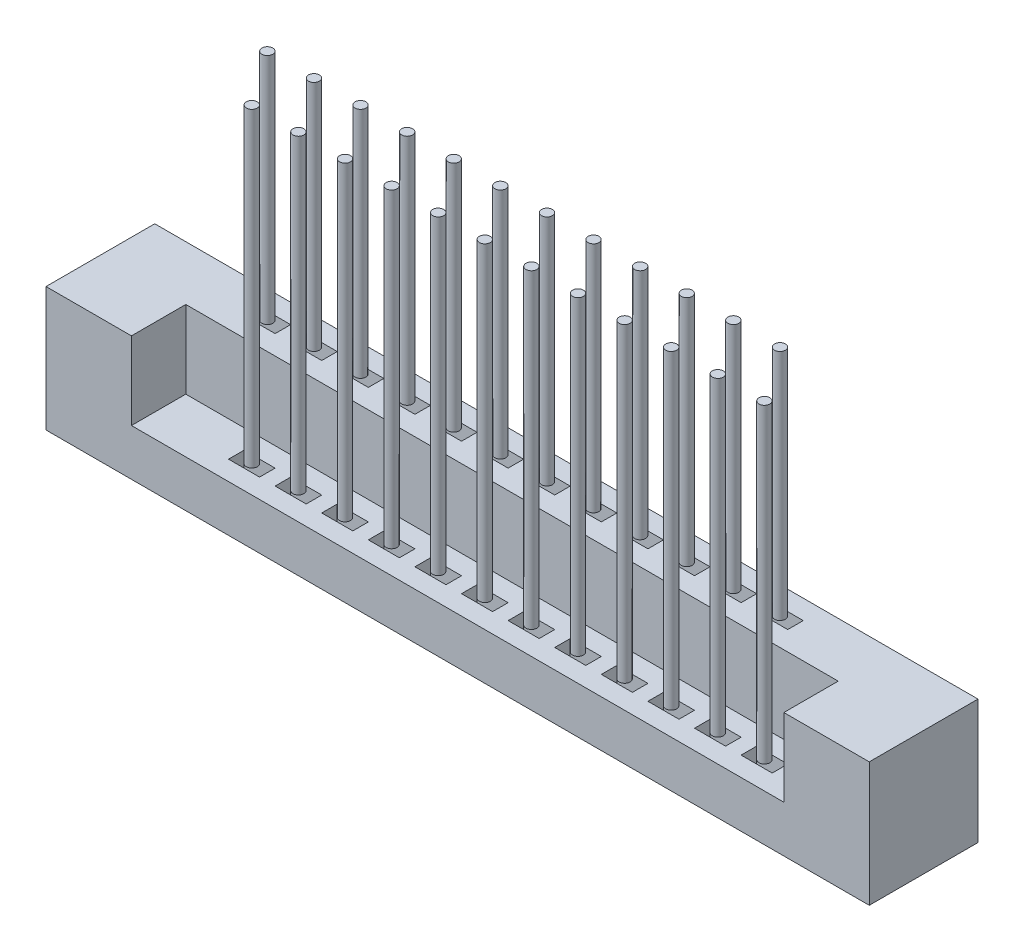
SolidWorks part; units mm, degrees
ref_plane "Front Plane" through (0, 0, 0) normal (0, 0, 1) x (1, 0, 0)
ref_plane "Top Plane" through (0, 0, 0) normal (0, 1, 0) x (1, 0, 0)
ref_plane "Right Plane" through (0, 0, 0) normal (1, 0, 0) x (0, 0, -1)
sketch "Sketch1" plane through (0, 0, 0) normal (0, 1, 0) x (1, 0, 0)
  line L1 (0, 0) -> (53, 0)
  line L2 (0, 0) -> (0, 7)
  line L3 (0, 7) -> (53, 7)
  line L4 (53, 0) -> (53, 7)
  dimension "D1" = 53
  dimension "D2" = 7
extrude "Boss-Extrude2" add sketch "Sketch1" along normal blind 8
sketch "Sketch2" plane through (0, 8, 0) normal (0, 1, 0) x (1, 0, 0)
  line L0 (53, 0) -> (53, 7) construction
  line L1 (47.5, 3.5) -> (5.5, 3.5)
  line L2 (47.5, 3.5) -> (47.5, 0)
  line L3 (47.5, 0) -> (5.5, 0)
  line L4 (5.5, 3.5) -> (5.5, 0)
  line L5 (0, 7) -> (0, 0) construction
  line L6 (53, 7) -> (0, 7) construction
  dimension "D1" = 42
  dimension "D2" = 5.5
  dimension "D3" = 5.5
  dimension "D4" = 3.5
  dimension "D5" = 3.5
extrude "Cut-Extrude1" cut sketch "Sketch2" against normal blind 5
sketch "Sketch3" plane through (0, 8, 0) normal (0, 1, 0) x (1, 0, 0)
  line L0 (47.5, 0) -> (47.5, 3.5) construction
  line L5 (45.5, 2.25) -> (43.5, 2.25)
  line L6 (45.5, 2.25) -> (45.5, 1.25)
  line L7 (45.5, 1.25) -> (43.5, 1.25)
  line L8 (43.5, 2.25) -> (43.5, 1.25)
  line L9 (43, 5.75) -> (41, 5.75)
  line L10 (43, 5.75) -> (43, 4.75)
  line L11 (43, 4.75) -> (41, 4.75)
  line L12 (41, 5.75) -> (41, 4.75)
  line L13 (53, 0) -> (53, 7) construction
  line L14 (5.5, 0) -> (47.5, 0) construction
  line L15 (47.5, 3.5) -> (5.5, 3.5) construction
  line L16 (53, 7) -> (0, 7) construction
  line L17 (42.5, 2.25) -> (42.5, 1.25)
  line L18 (42.5, 2.25) -> (40.5, 2.25)
  line L19 (40.5, 2.25) -> (40.5, 1.25)
  line L20 (42.5, 1.25) -> (40.5, 1.25)
  line L21 (40, 5.75) -> (40, 4.75)
  line L22 (40, 5.75) -> (38, 5.75)
  line L23 (38, 5.75) -> (38, 4.75)
  line L24 (40, 4.75) -> (38, 4.75)
  line L25 (39.5, 2.25) -> (39.5, 1.25)
  line L26 (39.5, 2.25) -> (37.5, 2.25)
  line L27 (37.5, 2.25) -> (37.5, 1.25)
  line L28 (39.5, 1.25) -> (37.5, 1.25)
  line L29 (37, 5.75) -> (37, 4.75)
  line L30 (37, 5.75) -> (35, 5.75)
  line L31 (35, 5.75) -> (35, 4.75)
  line L32 (37, 4.75) -> (35, 4.75)
  line L33 (36.5, 2.25) -> (36.5, 1.25)
  line L34 (36.5, 2.25) -> (34.5, 2.25)
  line L35 (34.5, 2.25) -> (34.5, 1.25)
  line L36 (36.5, 1.25) -> (34.5, 1.25)
  line L37 (34, 5.75) -> (34, 4.75)
  line L38 (34, 5.75) -> (32, 5.75)
  line L39 (32, 5.75) -> (32, 4.75)
  line L40 (34, 4.75) -> (32, 4.75)
  line L41 (33.5, 2.25) -> (33.5, 1.25)
  line L42 (33.5, 2.25) -> (31.5, 2.25)
  line L43 (31.5, 2.25) -> (31.5, 1.25)
  line L44 (33.5, 1.25) -> (31.5, 1.25)
  line L45 (31, 5.75) -> (31, 4.75)
  line L46 (31, 5.75) -> (29, 5.75)
  line L47 (29, 5.75) -> (29, 4.75)
  line L48 (31, 4.75) -> (29, 4.75)
  line L49 (30.5, 2.25) -> (30.5, 1.25)
  line L50 (30.5, 2.25) -> (28.5, 2.25)
  line L51 (28.5, 2.25) -> (28.5, 1.25)
  line L52 (30.5, 1.25) -> (28.5, 1.25)
  line L53 (28, 5.75) -> (28, 4.75)
  line L54 (28, 5.75) -> (26, 5.75)
  line L55 (26, 5.75) -> (26, 4.75)
  line L56 (28, 4.75) -> (26, 4.75)
  line L57 (27.5, 2.25) -> (27.5, 1.25)
  line L58 (27.5, 2.25) -> (25.5, 2.25)
  line L59 (25.5, 2.25) -> (25.5, 1.25)
  line L60 (27.5, 1.25) -> (25.5, 1.25)
  line L61 (25, 5.75) -> (25, 4.75)
  line L62 (25, 5.75) -> (23, 5.75)
  line L63 (23, 5.75) -> (23, 4.75)
  line L64 (25, 4.75) -> (23, 4.75)
  line L65 (24.5, 2.25) -> (24.5, 1.25)
  line L66 (24.5, 2.25) -> (22.5, 2.25)
  line L67 (22.5, 2.25) -> (22.5, 1.25)
  line L68 (24.5, 1.25) -> (22.5, 1.25)
  line L69 (22, 5.75) -> (22, 4.75)
  line L70 (22, 5.75) -> (20, 5.75)
  line L71 (20, 5.75) -> (20, 4.75)
  line L72 (22, 4.75) -> (20, 4.75)
  line L73 (21.5, 2.25) -> (21.5, 1.25)
  line L74 (21.5, 2.25) -> (19.5, 2.25)
  line L75 (19.5, 2.25) -> (19.5, 1.25)
  line L76 (21.5, 1.25) -> (19.5, 1.25)
  line L77 (19, 5.75) -> (19, 4.75)
  line L78 (19, 5.75) -> (17, 5.75)
  line L79 (17, 5.75) -> (17, 4.75)
  line L80 (19, 4.75) -> (17, 4.75)
  line L81 (18.5, 2.25) -> (18.5, 1.25)
  line L82 (18.5, 2.25) -> (16.5, 2.25)
  line L83 (16.5, 2.25) -> (16.5, 1.25)
  line L84 (18.5, 1.25) -> (16.5, 1.25)
  line L85 (16, 5.75) -> (16, 4.75)
  line L86 (16, 5.75) -> (14, 5.75)
  line L87 (14, 5.75) -> (14, 4.75)
  line L88 (16, 4.75) -> (14, 4.75)
  line L89 (15.5, 2.25) -> (15.5, 1.25)
  line L90 (15.5, 2.25) -> (13.5, 2.25)
  line L91 (13.5, 2.25) -> (13.5, 1.25)
  line L92 (15.5, 1.25) -> (13.5, 1.25)
  line L93 (13, 5.75) -> (13, 4.75)
  line L94 (13, 5.75) -> (11, 5.75)
  line L95 (11, 5.75) -> (11, 4.75)
  line L96 (13, 4.75) -> (11, 4.75)
  line L97 (12.5, 2.25) -> (12.5, 1.25)
  line L98 (12.5, 2.25) -> (10.5, 2.25)
  line L99 (10.5, 2.25) -> (10.5, 1.25)
  line L100 (12.5, 1.25) -> (10.5, 1.25)
  line L101 (10, 5.75) -> (10, 4.75)
  line L102 (10, 5.75) -> (8, 5.75)
  line L103 (8, 5.75) -> (8, 4.75)
  line L104 (10, 4.75) -> (8, 4.75)
  line L105 (5.5, 3.5) -> (5.5, 0) construction
  dimension "D1" = 2
  dimension "D2" = 1
  dimension "D3" = 1
  dimension "D4" = 2
  dimension "D5" = 2
  dimension "D6" = 10
  dimension "D7" = 1.25
  dimension "D8" = 1.25
  dimension "D9" = 1.25
  dimension "D11" = 5
  dimension "D10" = 12
extrude "Cut-Extrude2" cut sketch "Sketch3" against normal blind 2
sketch "Sketch4" plane through (0, 3, 0) normal (0, 1, 0) x (1, 0, 0)
  line L0 (47.5, 0) -> (47.5, 3.5) construction
  line L1 (45.5, 2.25) -> (43.5, 2.25)
  line L2 (45.5, 2.25) -> (45.5, 1.25)
  line L3 (45.5, 1.25) -> (43.5, 1.25)
  line L4 (43.5, 2.25) -> (43.5, 1.25)
  line L5 (5.5, 0) -> (47.5, 0) construction
  line L6 (42.5, 2.25) -> (42.5, 1.25)
  line L7 (42.5, 2.25) -> (40.5, 2.25)
  line L8 (40.5, 2.25) -> (40.5, 1.25)
  line L9 (42.5, 1.25) -> (40.5, 1.25)
  line L10 (39.5, 2.25) -> (39.5, 1.25)
  line L11 (39.5, 2.25) -> (37.5, 2.25)
  line L12 (37.5, 2.25) -> (37.5, 1.25)
  line L13 (39.5, 1.25) -> (37.5, 1.25)
  line L14 (36.5, 2.25) -> (36.5, 1.25)
  line L15 (36.5, 2.25) -> (34.5, 2.25)
  line L16 (34.5, 2.25) -> (34.5, 1.25)
  line L17 (36.5, 1.25) -> (34.5, 1.25)
  line L18 (33.5, 2.25) -> (33.5, 1.25)
  line L19 (33.5, 2.25) -> (31.5, 2.25)
  line L20 (31.5, 2.25) -> (31.5, 1.25)
  line L21 (33.5, 1.25) -> (31.5, 1.25)
  line L22 (30.5, 2.25) -> (30.5, 1.25)
  line L23 (30.5, 2.25) -> (28.5, 2.25)
  line L24 (28.5, 2.25) -> (28.5, 1.25)
  line L25 (30.5, 1.25) -> (28.5, 1.25)
  line L26 (27.5, 2.25) -> (27.5, 1.25)
  line L27 (27.5, 2.25) -> (25.5, 2.25)
  line L28 (25.5, 2.25) -> (25.5, 1.25)
  line L29 (27.5, 1.25) -> (25.5, 1.25)
  line L30 (24.5, 2.25) -> (24.5, 1.25)
  line L31 (24.5, 2.25) -> (22.5, 2.25)
  line L32 (22.5, 2.25) -> (22.5, 1.25)
  line L33 (24.5, 1.25) -> (22.5, 1.25)
  line L34 (21.5, 2.25) -> (21.5, 1.25)
  line L35 (21.5, 2.25) -> (19.5, 2.25)
  line L36 (19.5, 2.25) -> (19.5, 1.25)
  line L37 (21.5, 1.25) -> (19.5, 1.25)
  line L38 (18.5, 2.25) -> (18.5, 1.25)
  line L39 (18.5, 2.25) -> (16.5, 2.25)
  line L40 (16.5, 2.25) -> (16.5, 1.25)
  line L41 (18.5, 1.25) -> (16.5, 1.25)
  line L42 (15.5, 2.25) -> (15.5, 1.25)
  line L43 (15.5, 2.25) -> (13.5, 2.25)
  line L44 (13.5, 2.25) -> (13.5, 1.25)
  line L45 (15.5, 1.25) -> (13.5, 1.25)
  line L46 (12.5, 2.25) -> (12.5, 1.25)
  line L47 (12.5, 2.25) -> (10.5, 2.25)
  line L48 (10.5, 2.25) -> (10.5, 1.25)
  line L49 (12.5, 1.25) -> (10.5, 1.25)
  line L50 (5.5, 3.5) -> (5.5, 0) construction
  dimension "D1" = 2
  dimension "D2" = 1
  dimension "D3" = 2
  dimension "D4" = 1.25
  dimension "D6" = 5
  dimension "D5" = 12
extrude "Cut-Extrude3" cut sketch "Sketch4" against normal blind 2
sketch "Sketch5" plane through (0, 3, 0) normal (0, 1, 0) x (1, 0, 0)
  line L0 (45.5, 2.25) -> (43.5, 2.25) construction
  line L1 (45.5, 1.25) -> (45.5, 2.25) construction
  line L2 (10.5, 2.25) -> (10.5, 1.25) construction
  circle A0 centre (44.5, 1.75) radius 0.35
  circle A1 centre (41.5, 1.75) radius 0.35
  circle A2 centre (38.5, 1.75) radius 0.35
  circle A3 centre (35.5, 1.75) radius 0.35
  circle A4 centre (32.5, 1.75) radius 0.35
  circle A5 centre (29.5, 1.75) radius 0.35
  circle A6 centre (26.5, 1.75) radius 0.35
  circle A7 centre (23.5, 1.75) radius 0.35
  circle A8 centre (20.5, 1.75) radius 0.35
  circle A9 centre (17.5, 1.75) radius 0.35
  circle A10 centre (14.5, 1.75) radius 0.35
  circle A11 centre (11.5, 1.75) radius 0.35
  dimension "D1" = 0.7
  dimension "D2" = 0.5
  dimension "D3" = 1
  dimension "D5" = 1
  dimension "D4" = 12
extrude "Boss-Extrude8" add sketch "Sketch5" along normal blind 20 separate body
sketch "Sketch6" plane through (0, 8, 0) normal (0, 1, 0) x (1, 0, 0)
  line L0 (43, 4.75) -> (43, 5.75) construction
  line L1 (43, 5.75) -> (41, 5.75) construction
  line L2 (8, 5.75) -> (8, 4.75) construction
  circle A0 centre (42, 5.25) radius 0.35
  circle A1 centre (39, 5.25) radius 0.35
  circle A2 centre (36, 5.25) radius 0.35
  circle A3 centre (33, 5.25) radius 0.35
  circle A4 centre (30, 5.25) radius 0.35
  circle A5 centre (27, 5.25) radius 0.35
  circle A6 centre (24, 5.25) radius 0.35
  circle A7 centre (21, 5.25) radius 0.35
  circle A8 centre (18, 5.25) radius 0.35
  circle A9 centre (15, 5.25) radius 0.35
  circle A10 centre (12, 5.25) radius 0.35
  circle A11 centre (9, 5.25) radius 0.35
  dimension "D1" = 0.7
  dimension "D2" = 1
  dimension "D3" = 0.5
  dimension "D5" = 1
  dimension "D4" = 12
extrude "Boss-Extrude11" add sketch "Sketch6" along normal blind 15 separate body
